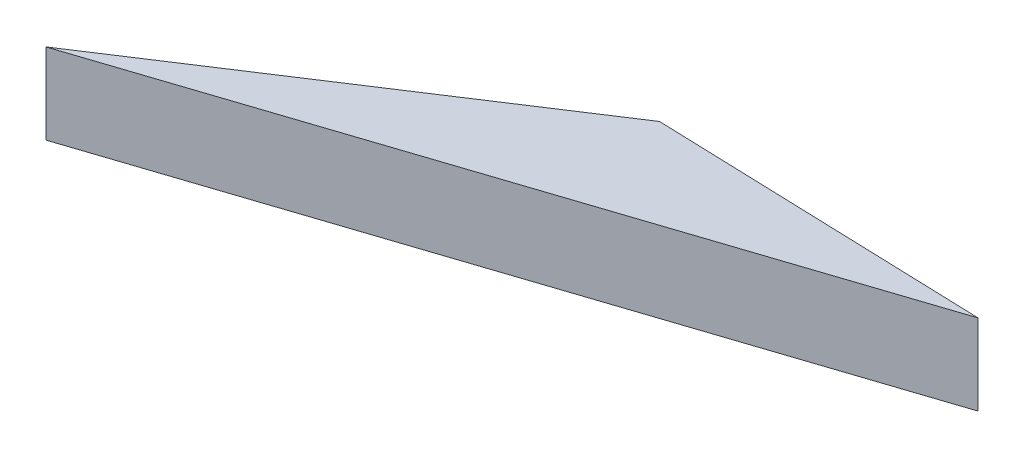
SolidWorks part; units mm, degrees
material "Pine"
ref_plane "Front Plane" through (0, 0, 0) normal (0, 0, 1) x (1, 0, 0)
ref_plane "Top Plane" through (0, 0, 0) normal (0, 1, 0) x (1, 0, 0)
ref_plane "Right Plane" through (0, 0, 0) normal (1, 0, 0) x (0, 0, -1)
sketch "Sketch1" plane through (0, 0, 0) normal (0, 1, 0) x (1, 0, 0)
  line L1 (0, 0) -> (2300, 0)
  line L2 (0, 0) -> (0, 150)
  line L3 (0, 150) -> (2300, 150)
  line L4 (2300, 0) -> (2300, 150)
  dimension "D1" = 150
  dimension "D2" = 2300
extrude "Boss-Extrude1" add sketch "Sketch1" along normal blind 50
sketch "Sketch2" plane through (0, 50, 0) normal (0, 1, 0) x (1, 0, 0)
  line L0 (0, 0) -> (230, 150)
  line L1 (2300, 150) -> (0, 150) construction
  line L2 (230, 150) -> (433.953, 143.2746)
  line L8 (433.953, 143.2746) -> (0, 0)
  point P5 (443.5187, 131.6564)
  point P7 (246.4268, 150)
  dimension "D1" = 230
  dimension "D2" = 215
  dimension "D3" = 433.953
extrude "Cut-Extrude1" cut sketch "Sketch2" against normal through all flip side to cut
